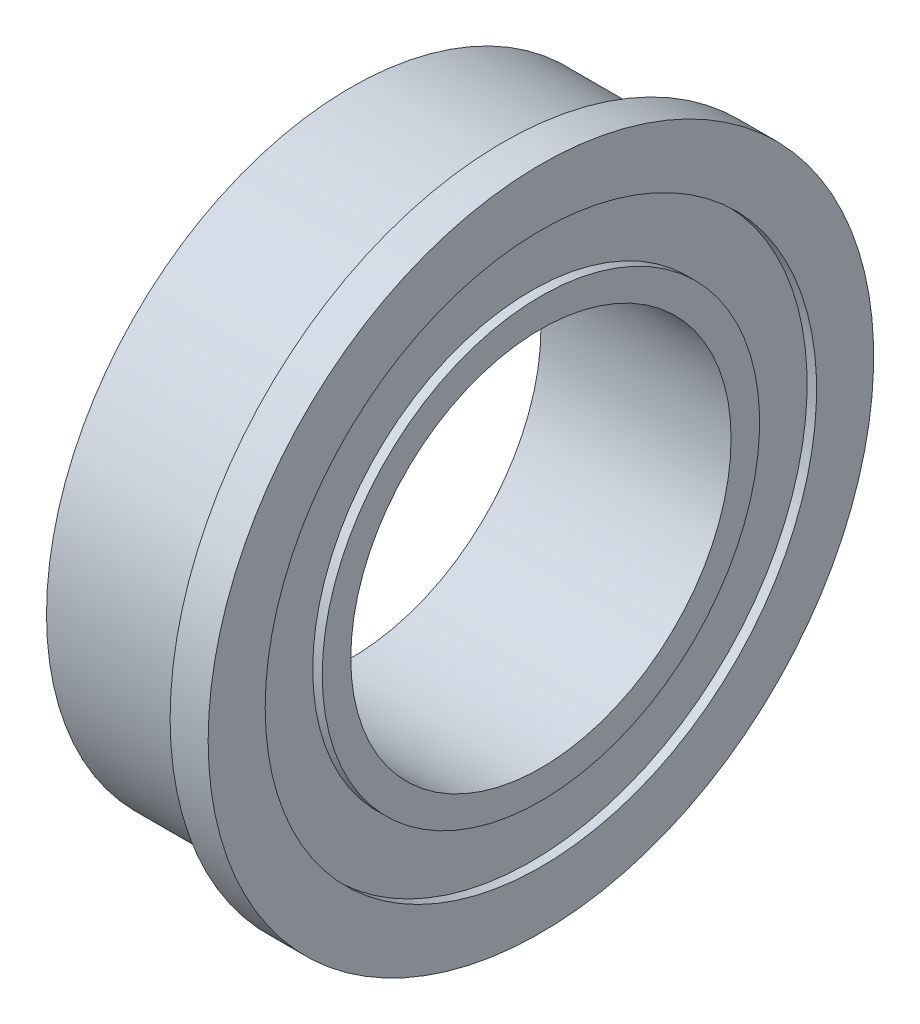
SolidWorks part; units mm, degrees
ref_plane "前视基准面" through (0, 0, 0) normal (0, 0, 1) x (1, 0, 0)
ref_plane "上视基准面" through (0, 0, 0) normal (0, 1, 0) x (1, 0, 0)
ref_plane "右视基准面" through (0, 0, 0) normal (1, 0, 0) x (0, 0, -1)
other "Configuration Table"
sketch "草图1" plane through (0, 0, 0) normal (0, 1, 0) x (1, 0, 0)
  line L0 (0, 0) -> (10, 0) construction
  line L1 (10, 0) -> (10, 10) construction
  line L2 (10, 10) -> (0, 10)
  line L3 (0, 10) -> (0, 0) construction
  line L4 (10, 10) -> (10, 17.5)
  line L5 (10, 17.5) -> (8, 17.5)
  line L6 (8, 17.5) -> (8, 16)
  line L7 (8, 16) -> (0, 16)
  line L8 (0, 16) -> (0, 10)
  line L9 (0, 13) -> (10, 13) construction
  line L10 (10, 11.5) -> (9.5, 11.5)
  line L11 (10, 11.5) -> (10, 14.5)
  line L12 (10, 14.5) -> (9.5, 14.5)
  line L13 (9.5, 11.5) -> (9.5, 14.5)
  line L15 (0, 11.5) -> (0.5, 11.5)
  line L16 (0, 11.5) -> (0, 14.5)
  line L17 (0, 14.5) -> (0.5, 14.5)
  line L18 (0.5, 11.5) -> (0.5, 14.5)
  dimension "D1" = 20
  dimension "D2" = 35
  dimension "D3" = 32
  dimension "D4" = 10
  dimension "D5" = 2
  dimension "D6" = 0.5
  dimension "D7" = 3
  dimension "D8" = 0.5
  dimension "D9" = 3
revolve "旋转1" add sketch "草图1" angle 360 about L0
